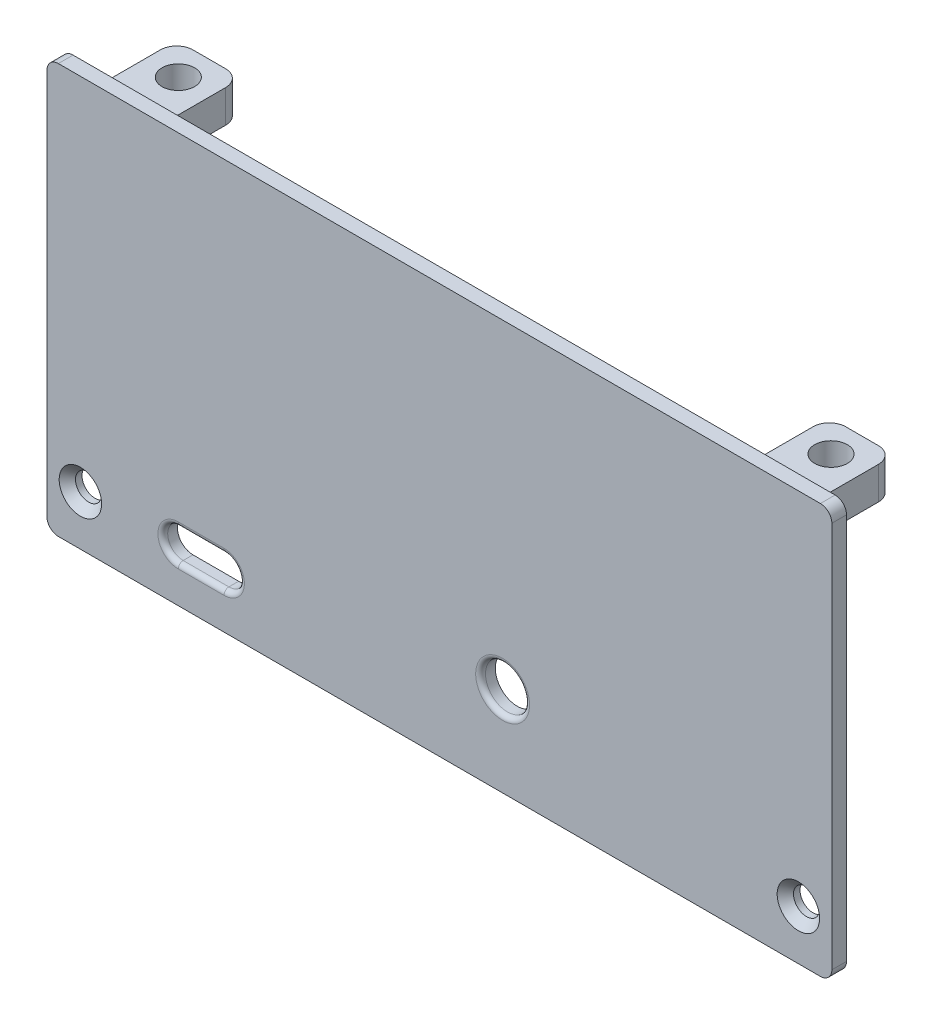
SolidWorks part; units mm, degrees
ref_plane "Front Plane" through (0, 0, 0) normal (0, 0, 1) x (1, 0, 0)
ref_plane "Top Plane" through (0, 0, 0) normal (0, 1, 0) x (1, 0, 0)
ref_plane "Right Plane" through (0, 0, 0) normal (1, 0, 0) x (0, 0, -1)
sketch "Sketch1" plane through (0, 0, 0) normal (0, 0, 1) x (1, 0, 0)
  line L1 (0, 0) -> (97, 0)
  line L2 (0, 0) -> (0, -51)
  line L3 (0, -51) -> (97, -51)
  line L4 (97, 0) -> (97, -51)
  circle A0 centre (92.5, -44.5) radius 1.6
  circle A1 centre (4.5, -44.5) radius 1.6
  dimension "D3" = 4.5
  dimension "D6" = 3.2
  dimension "D1" = 97
  dimension "D2" = 51
  dimension "D4" = 6.5
  dimension "D5" = 4.5
extrude "Boss-Extrude1" add sketch "Sketch1" along normal blind 1.8
fillet "Fillet1" radius 2 4 edges at (0, 0, 0.9) (0, -51, 0.9) (97, -51, 0.9) (97, 0, 0.9)
ref_plane "Plane1" through (0, -2.5, 0) normal (0, 1, 0) x (1, 0, 0)
sketch "Sketch4" plane through (0, -2.5, 0) normal (0, 1, 0) x (1, 0, 0)
  line L0 (97, 0) -> (97, -1.8) construction
  line L1 (84.5, 0) -> (92.5, 0)
  line L2 (84.5, 0) -> (84.5, 10)
  line L3 (84.5, 10) -> (92.5, 10)
  line L4 (92.5, 0) -> (92.5, 10)
  line L5 (95, 0) -> (2, 0) construction
  line L6 (95, -1.8) -> (2, -1.8) construction
  circle A0 centre (88.5, 6.2) radius 2
  point P4 (97, -0.9)
  point P11 (97, -0.9)
  dimension "D4" = 4
  dimension "D1" = 10
  dimension "D2" = 4.5
  dimension "D3" = 4
  dimension "D5" = 8.5
  dimension "D6" = 8
extrude "Boss-Extrude3" add sketch "Sketch4" against normal blind 4
fillet "Fillet2" radius 2 2 edges at (84.5, -4.5, -10) (92.5, -4.5, -10)
ref_plane "Plane2" through (48.5, 0, 0) normal (1, 0, 0) x (0, 0, -1)
mirror "Mirror1" about plane through (48.5, 0, 0) normal (1, 0, 0) of "Fillet2", "Boss-Extrude3"
sketch "Sketch5" plane through (0, 0, 0) normal (0, 0, -1) x (-1, 0, 0)
  line L0 (-95, 0) -> (-2, 0) construction
  line L1 (-86.65, -10) -> (-10.35, -10)
  line L2 (-87.15, -10.5) -> (-87.15, -30.8)
  line L3 (-86.65, -31.3) -> (-10.35, -31.3)
  line L4 (-9.85, -10.5) -> (-9.85, -30.8)
  line L5 (-97, -49) -> (-97, -2) construction
  line L6 (-89.15, -10) -> (-89.15, -31.3)
  line L7 (-87.15, -33.3) -> (-9.85, -33.3)
  line L8 (-7.85, -10) -> (-7.85, -31.3)
  line L9 (-87.15, -8) -> (-9.85, -8)
  line L10 (-7.85, -8) -> (-7.85, -33.3) construction
  line L11 (-89.15, -8) -> (-7.85, -8) construction
  line L12 (-89.15, -33.3) -> (-7.85, -33.3) construction
  line L13 (-89.15, -8) -> (-89.15, -33.3) construction
  line L15 (-87.15, -10) -> (-9.85, -10) construction
  line L16 (-87.15, -10) -> (-87.15, -31.3) construction
  line L17 (-87.15, -31.3) -> (-9.85, -31.3) construction
  line L18 (-9.85, -10) -> (-9.85, -31.3) construction
  arc A0 (-7.85, -10) -> (-9.85, -8) centre (-9.85, -10) ccw
  arc A1 (-9.85, -33.3) -> (-7.85, -31.3) centre (-9.85, -31.3) ccw
  arc A2 (-89.15, -31.3) -> (-87.15, -33.3) centre (-87.15, -31.3) ccw
  arc A3 (-89.15, -10) -> (-87.15, -8) centre (-87.15, -10) cw
  arc A4 (-86.65, -10) -> (-87.15, -10.5) centre (-87.15, -10) ccw
  arc A5 (-87.15, -30.8) -> (-86.65, -31.3) centre (-87.15, -31.3) ccw
  arc A6 (-10.35, -31.3) -> (-9.85, -30.8) centre (-9.85, -31.3) ccw
  arc A7 (-9.85, -10.5) -> (-10.35, -10) centre (-9.85, -10) ccw
  dimension "D6" = 2
  dimension "D7" = 1
  dimension "D1" = 10
  dimension "D2" = 21.3
  dimension "D3" = 77.3
  dimension "D4" = 9.85
  dimension "D5" = 2
extrude "Boss-Extrude4" add sketch "Sketch5" along normal blind 7
sketch "Sketch7" plane through (0, 0, 1.8) normal (0, 0, 1) x (1, 0, 0)
  line L0 (97, -49) -> (97, -2) construction
  line L1 (2, -51) -> (95, -51) construction
  circle A0 centre (56.25, -39.6) radius 2.7
  dimension "D3" = 5.4
  dimension "D1" = 40.75
  dimension "D2" = 11.4
extrude "Cut-Extrude3" cut sketch "Sketch7" against normal through all
sketch "Sketch8" plane through (0, 0, 1.8) normal (0, 0, 1) x (1, 0, 0)
  line L0 (16.5, -44.2) -> (22.1, -44.2) construction
  line L1 (16.5, -42.3) -> (22.1, -42.3)
  line L2 (16.5, -46.1) -> (22.1, -46.1)
  line L3 (2, -51) -> (95, -51) construction
  line L4 (0, -2) -> (0, -49) construction
  arc A0 (16.5, -42.3) -> (16.5, -46.1) centre (16.5, -44.2) ccw
  arc A1 (22.1, -46.1) -> (22.1, -42.3) centre (22.1, -44.2) ccw
  point P2 (19.3, -44.2)
  dimension "D3" = 9.4
  dimension "D1" = 6.8
  dimension "D2" = 16.5
  dimension "D4" = 3.8
extrude "Cut-Extrude4" cut sketch "Sketch8" against normal through all
fillet "Fillet3" radius 0.6 5 edges at (24, -44.2, 1.8) (19.3, -46.1, 1.8) (14.6, -44.2, 1.8) (58.95, -39.6, 1.8) (19.3, -42.3, 1.8)
chamfer "Chamfer1" distance 1 angle 45 2 edges at (94.1, -44.5, 1.8) (6.1, -44.5, 1.8)
sketch "Sketch9" plane through (0, 0, 1.8) normal (0, 0, 1) x (1, 0, 0)
  line L0 (97, -49) -> (97, -2) construction
  line L1 (0, 0) -> (97, 0)
  line L2 (0, 0) -> (0, -51)
  line L3 (0, -51) -> (97, -51)
  line L4 (97, 0) -> (97, -51)
  line L5 (2, -51) -> (95, -51) construction
  line L6 (0.4, -1.8) -> (0.4, -49.2)
  line L7 (1.8, -50.6) -> (95.2, -50.6)
  line L8 (96.6, -1.8) -> (96.6, -49.2)
  line L9 (1.8, -0.4) -> (95.2, -0.4)
  line L10 (0.4, -0.4) -> (0.4, -50.6) construction
  line L11 (0.4, -0.4) -> (96.6, -0.4) construction
  line L12 (96.6, -0.4) -> (96.6, -50.6) construction
  line L13 (0.4, -50.6) -> (96.6, -50.6) construction
  arc A0 (0.4, -1.8) -> (1.8, -0.4) centre (1.8, -1.8) cw
  arc A1 (96.6, -1.8) -> (95.2, -0.4) centre (95.2, -1.8) ccw
  arc A2 (95.2, -50.6) -> (96.6, -49.2) centre (95.2, -49.2) ccw
  arc A3 (0.4, -49.2) -> (1.8, -50.6) centre (1.8, -49.2) ccw
  dimension "D2" = 1.4
  dimension "D1" = 0.4
extrude "Cut-Extrude5" cut sketch "Sketch9" against normal through all
